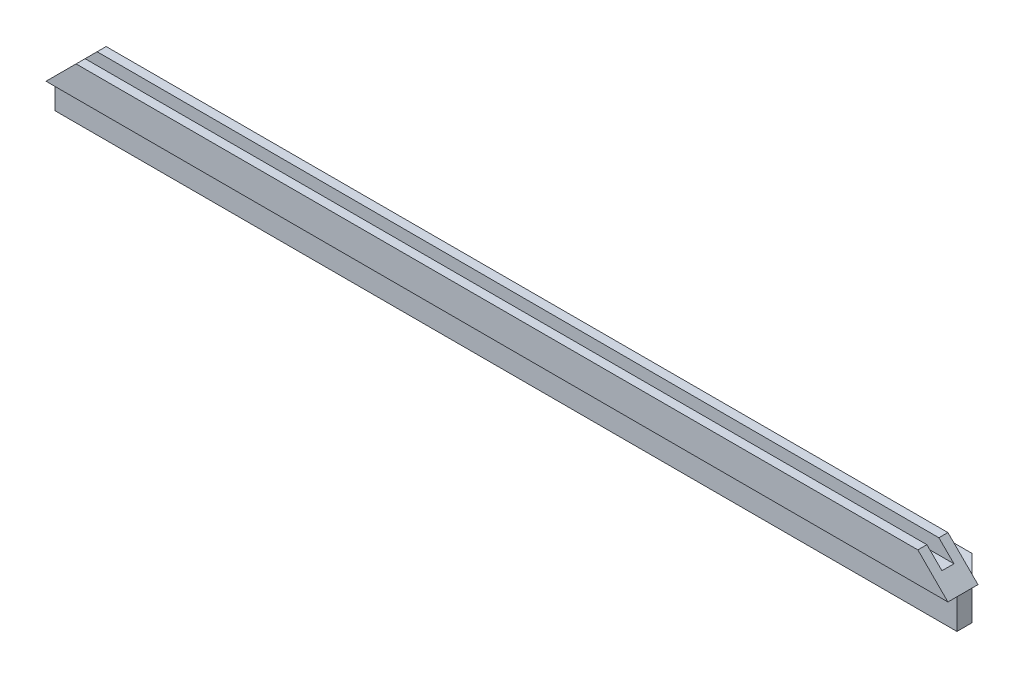
SolidWorks part; units mm, degrees
ref_plane "前视基准面" through (0, 0, 0) normal (0, 0, 1) x (1, 0, 0)
ref_plane "上视基准面" through (0, 0, 0) normal (0, 1, 0) x (1, 0, 0)
ref_plane "右视基准面" through (0, 0, 0) normal (1, 0, 0) x (0, 0, -1)
other "Configuration Table"
sketch "草图2" plane through (0, 0, 0) normal (0, 1, 0) x (1, 0, 0)
  line L0 (-130.6414, -36.9259) -> (169.3586, -36.9259)
  line L1 (-125.6414, -31.9259) -> (164.3586, -31.9259)
  line L2 (-130.6414, -36.9259) -> (-125.6414, -31.9259)
  line L3 (164.3586, -31.9259) -> (169.3586, -36.9259)
  dimension "D1" = 300
  dimension "D2" = 290
  dimension "D3" = 5
  dimension "D4" = 45
  dimension "D5" = 45
extrude "凸台-拉伸2" add sketch "草图2" along normal blind 4
ref_plane "基准面2" through (0, 2, 0) normal (0, 1, 0) x (1, 0, 0)
sketch "草图3" plane through (0, 4, 0) normal (0, 1, 0) x (1, 0, 0)
  line L0 (-130.6414, -36.9259) -> (-120.6414, -26.9259)
  line L1 (-130.6414, -36.9259) -> (169.3586, -36.9259)
  line L3 (-120.6414, -26.9259) -> (159.3586, -26.9259)
  line L5 (169.3586, -36.9259) -> (159.3586, -26.9259)
  dimension "D2" = 300
  dimension "D3" = 45
extrude "凸台-拉伸3" add sketch "草图3" along normal blind 3
mirror "镜向1" about plane through (0, 2, 0) normal (0, 1, 0) of "凸台-拉伸3"
sketch "草图5" plane through (0, 0, 36.9259) normal (0, 0, 1) x (1, 0, 0)
  line L1 (-130.6414, 7) -> (169.3586, 7)
  line L2 (-130.6414, 7) -> (-130.6414, -3)
  line L3 (-130.6414, -3) -> (169.3586, -3)
  line L4 (169.3586, 7) -> (169.3586, -3)
  dimension "D1" = 10
  dimension "D2" = 300
extrude "凸台-拉伸4" add sketch "草图5" along normal blind 5
ref_plane "基准面3" through (0, 0, 41.9259) normal (0, 0, 1) x (1, 0, 0)
sketch "草图7" plane through (0, 0, 41.9259) normal (0, 0, 1) x (1, 0, 0)
  line L1 (-130.6414, 7) -> (169.3586, 7)
  line L2 (-125.6414, 12) -> (164.3586, 12)
  line L3 (-125.6414, 12) -> (-130.6414, 7)
  line L4 (164.3586, 12) -> (169.3586, 7)
  dimension "D1" = 290
  dimension "D2" = 45
  dimension "D3" = 45
extrude "凸台-拉伸5" add sketch "草图7" against normal blind 4
ref_plane "基准面4" through (0, 0, 39.9259) normal (0, 0, -1) x (-1, 0, 0)
sketch "草图8" plane through (0, 0, 37.9259) normal (0, 0, -1) x (-1, 0, 0)
  line L0 (-169.3586, 7) -> (-159.3586, 17)
  line L1 (-169.3586, 7) -> (130.6414, 7)
  line L3 (-159.3586, 17) -> (120.6414, 17)
  line L5 (130.6414, 7) -> (120.6414, 17)
  dimension "D2" = 300
extrude "凸台-拉伸6" add sketch "草图8" along normal blind 3
mirror "镜向2" about plane through (0, 0, 39.9259) normal (0, 0, -1) of "凸台-拉伸6"
